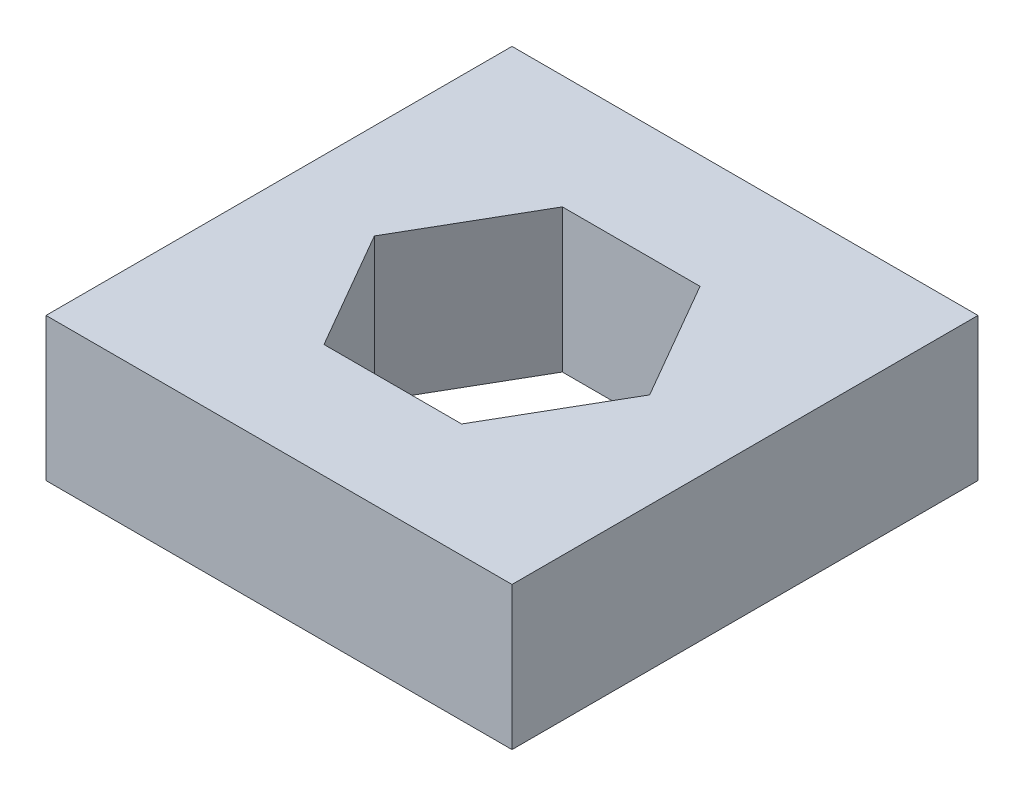
SolidWorks part; units mm, degrees
ref_plane "Plano frontal" through (0, 0, 0) normal (0, 0, 1) x (1, 0, 0)
ref_plane "Plano superior" through (0, 0, 0) normal (0, 1, 0) x (1, 0, 0)
ref_plane "Plano direito" through (0, 0, 0) normal (1, 0, 0) x (0, 0, -1)
sketch "Esboço1" plane through (0, 0, 0) normal (0, 1, 0) x (1, 0, 0)
  line L1 (1.4434, 2.5) -> (-1.4434, 2.5)
  line L2 (-1.4434, 2.5) -> (-2.8868, 0)
  line L3 (-2.8868, 0) -> (-1.4434, -2.5)
  line L4 (-1.4434, -2.5) -> (1.4434, -2.5)
  line L5 (1.4434, -2.5) -> (2.8868, 0)
  line L6 (2.8868, 0) -> (1.4434, 2.5)
  line L7 (-4.8868, -4.8868) -> (4.8868, -4.8868)
  line L8 (-4.8868, -4.8868) -> (-4.8868, 4.8868)
  line L9 (-4.8868, 4.8868) -> (4.8868, 4.8868)
  line L10 (4.8868, -4.8868) -> (4.8868, 4.8868)
  line L11 (-4.8868, -4.8868) -> (4.8868, 4.8868) construction
  line L12 (-4.8868, 4.8868) -> (4.8868, -4.8868) construction
  circle A0 centre (0, 0) radius 2.5 construction
  dimension "D1" = 5
  dimension "D2" = 2
extrude "Ressalto-extrusão1" add sketch "Esboço1" along normal blind 3
